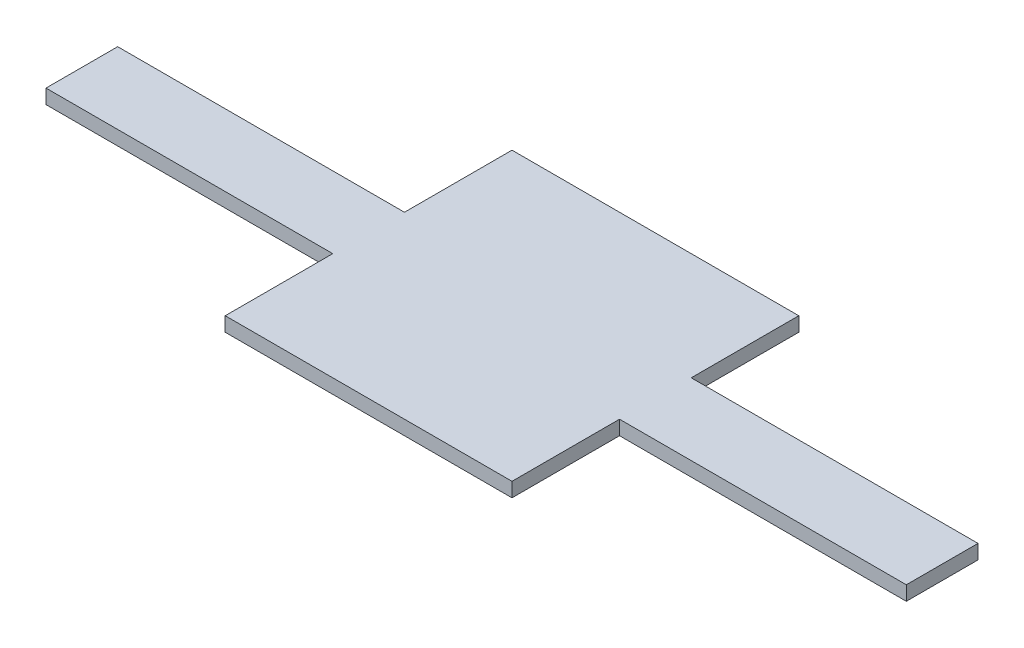
SolidWorks part; units mm, degrees
ref_plane "Alzado" through (0, 0, 0) normal (0, 0, 1) x (1, 0, 0)
ref_plane "Planta" through (0, 0, 0) normal (0, 1, 0) x (1, 0, 0)
ref_plane "Vista lateral" through (0, 0, 0) normal (1, 0, 0) x (0, 0, -1)
sketch "Croquis1" plane through (0, 0, 0) normal (0, 1, 0) x (1, 0, 0)
  line L1 (0, 0) -> (10, 0)
  line L2 (0, 0) -> (0, 10)
  line L3 (0, 10) -> (10, 10)
  line L4 (10, 0) -> (10, 10)
  dimension "D1" = 10
extrude "Saliente-Extruir1" add sketch "Croquis1" along normal blind 0.5
sketch "Croquis2" plane through (10, 0, 0) normal (1, 0, 0) x (0, 0, -1)
  line L0 (0, 0) -> (10, 0) construction
  line L1 (3.75, 0) -> (6.25, 0)
  line L2 (3.75, 0) -> (3.75, 0.5)
  line L3 (3.75, 0.5) -> (6.25, 0.5)
  line L4 (6.25, 0) -> (6.25, 0.5)
  line L5 (0, 0.5) -> (10, 0.5) construction
  line L6 (5, 0) -> (5, 0.5) construction
  dimension "D1" = 2.5
extrude "Saliente-Extruir2" add sketch "Croquis2" along normal blind 10 and the other way blind 20
